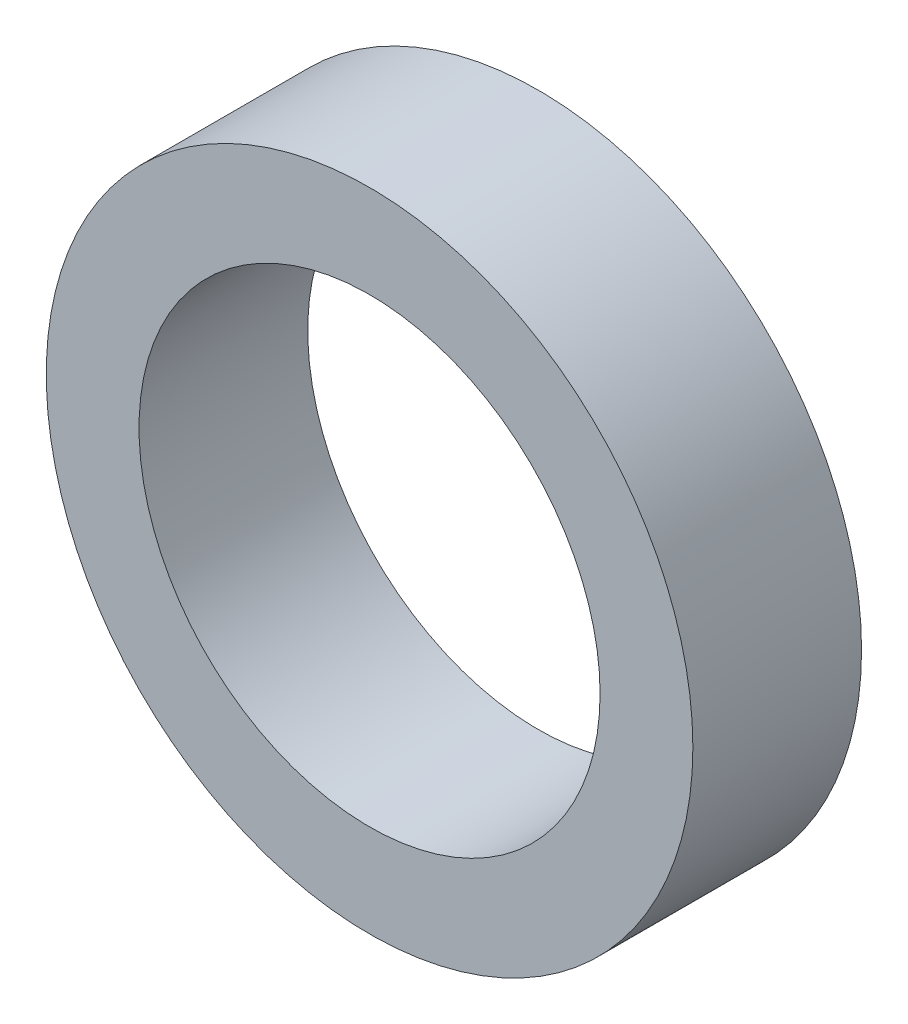
SolidWorks part; units mm, degrees
ref_plane "Front Plane" through (0, 0, 0) normal (0, 0, 1) x (1, 0, 0)
ref_plane "Top Plane" through (0, 0, 0) normal (0, 1, 0) x (1, 0, 0)
ref_plane "Right Plane" through (0, 0, 0) normal (1, 0, 0) x (0, 0, -1)
sketch "Sketch1" plane through (0, 0, 0) normal (0, 0, 1) x (1, 0, 0)
  circle A0 centre (0, 0) radius 5.75
  circle A1 centre (0, 0) radius 4.1
  dimension "D1" = 11.5
  dimension "D2" = 8.2
extrude "Boss-Extrude1" add sketch "Sketch1" along normal blind 3
